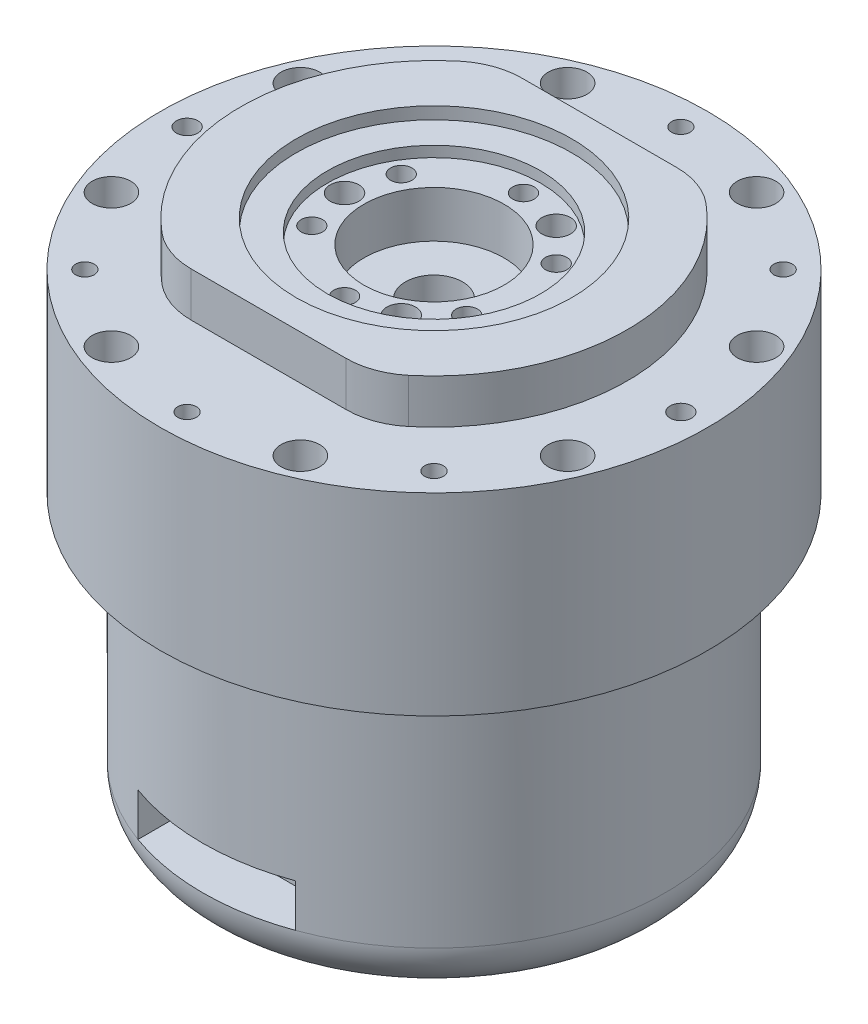
SolidWorks part; units mm, degrees
ref_plane "前视基准面" through (0, 0, 0) normal (0, 0, 1) x (1, 0, 0)
ref_plane "上视基准面" through (0, 0, 0) normal (0, 1, 0) x (1, 0, 0)
ref_plane "右视基准面" through (0, 0, 0) normal (1, 0, 0) x (0, 0, -1)
other "Configuration Table"
sketch "草图1" plane through (0, 0, 0) normal (0, 1, 0) x (1, 0, 0)
  line L0 (-38.25, 0) -> (38.25, 0) construction
  line L1 (-13.9782, 23.1) -> (13.9782, 23.1)
  line L2 (-13.9782, -23.1) -> (13.9782, -23.1)
  line L3 (0, 12.5) -> (0, 0) construction
  line L4 (0, 0) -> (6.25, 10.8253) construction
  line L5 (13.2026, 31.8738) -> (0, 0) construction
  line L6 (0, 0) -> (0, 34.5) construction
  circle A0 centre (0, 0) radius 12.5 construction
  circle A1 centre (0, 0) radius 38.25
  circle A2 centre (0, 0) radius 34.5 construction
  circle A3 centre (0, 0) radius 27
  circle A4 centre (0, 34.5) radius 1.3
  circle A5 centre (24.3952, 24.3952) radius 1.3
  circle A6 centre (34.5, 0) radius 1.3
  circle A7 centre (24.3952, -24.3952) radius 1.3
  circle A8 centre (0, -34.5) radius 1.3
  circle A9 centre (-24.3952, -24.3952) radius 1.3
  circle A10 centre (-34.5, 0) radius 1.3
  circle A11 centre (-24.3952, 24.3952) radius 1.3
  circle A12 centre (0, 12.5) radius 1.5
  circle A13 centre (10.8253, 6.25) radius 1.5
  circle A14 centre (10.8253, -6.25) radius 1.5
  circle A15 centre (0, -12.5) radius 1.5
  circle A16 centre (-10.8253, -6.25) radius 1.5
  circle A17 centre (-10.8253, 6.25) radius 1.5
  circle A18 centre (6.25, 10.8253) radius 2
  circle A19 centre (6.25, -10.8253) radius 2
  circle A20 centre (-12.5, 0) radius 2
  circle A21 centre (0, 0) radius 19.25
  circle A22 centre (0, 0) radius 14.9 construction
  circle A23 centre (0, 0) radius 9.8 construction
  circle A24 centre (13.2026, 31.8738) radius 2.7
  circle A25 centre (31.8738, 13.2026) radius 2.7
  circle A26 centre (31.8738, -13.2026) radius 2.7
  circle A27 centre (13.2026, -31.8738) radius 2.7
  circle A28 centre (-13.2026, -31.8738) radius 2.7
  circle A29 centre (-31.8738, -13.2026) radius 2.7
  circle A30 centre (-31.8738, 13.2026) radius 2.7
  circle A31 centre (-13.2026, 31.8738) radius 2.7
  point P30 (0, 0)
  point P43 (0, 0)
  point P50 (0, 0)
  point P70 (0, 0)
  dimension "D1" = 25
  dimension "D2" = 76.5
  dimension "D3" = 69
  dimension "D4" = 54
  dimension "D6" = 2.6
  dimension "D8" = 3
  dimension "D11" = 4
  dimension "D13" = 38.5
  dimension "D14" = 29.8
  dimension "D15" = 19.6
  dimension "D16" = 5.4
  dimension "D5" = 46.2
  dimension "D10" = 30
  dimension "D17" = 22.5
  dimension "D7" = 8
  dimension "D9" = 6
  dimension "D12" = 3
  dimension "D18" = 8
sketch "草图2" plane through (0, 0, 0) normal (0, 1, 0) x (1, 0, 0)
  circle A3 centre (0, 34.5) radius 1.3
  circle A4 centre (0, 34.5) radius 1.3
  circle A7 centre (0, 0) radius 38.25
  circle A8 centre (0, 0) radius 38.25
  circle A9 centre (-24.3952, 24.3952) radius 1.3
  circle A10 centre (-24.3952, 24.3952) radius 1.3
  circle A11 centre (-34.5, 0) radius 1.3
  circle A12 centre (-34.5, 0) radius 1.3
  circle A13 centre (-24.3952, -24.3952) radius 1.3
  circle A14 centre (-24.3952, -24.3952) radius 1.3
  circle A15 centre (0, -34.5) radius 1.3
  circle A16 centre (0, -34.5) radius 1.3
  circle A17 centre (24.3952, -24.3952) radius 1.3
  circle A18 centre (24.3952, -24.3952) radius 1.3
  circle A19 centre (34.5, 0) radius 1.3
  circle A20 centre (34.5, 0) radius 1.3
  circle A21 centre (24.3952, 24.3952) radius 1.3
  circle A22 centre (24.3952, 24.3952) radius 1.3
  dimension "D2" = 0
  dimension "D4" = 0
  dimension "D5" = 0
  dimension "D6" = 0
  dimension "D7" = 0
  dimension "D8" = 0
  dimension "D9" = 0
  dimension "D10" = 0
  dimension "D11" = 0
extrude "凸台-拉伸1" add sketch "草图2" along normal blind 27
cosmetic thread "装饰螺纹线2" parameters "D2"=3
cosmetic thread "装饰螺纹线3" parameters "D2"=3
cosmetic thread "装饰螺纹线4" parameters "D2"=3
cosmetic thread "装饰螺纹线5" parameters "D2"=3
cosmetic thread "装饰螺纹线6" parameters "D2"=3
cosmetic thread "装饰螺纹线7" parameters "D2"=3
sketch "草图3" plane through (0, 27, 0) normal (0, 1, 0) x (1, 0, 0)
  line L0 (-13.9782, 23.1) -> (13.9782, 23.1) construction
  line L1 (-13.9782, 23.1) -> (13.9782, 23.1)
  line L2 (-13.9782, -23.1) -> (13.9782, -23.1) construction
  line L3 (-13.9782, -23.1) -> (13.9782, -23.1)
  circle A0 centre (0, 0) radius 27 construction
  arc A1 (-13.9782, 23.1) -> (-13.9782, -23.1) centre (0, 0) ccw
  arc A2 (13.9782, -23.1) -> (13.9782, 23.1) centre (0, 0) ccw
extrude "凸台-拉伸2" add sketch "草图3" along normal blind 6.2
sketch "草图4" plane through (0, 33.2, 0) normal (0, 1, 0) x (1, 0, 0)
  circle A0 centre (0, 0) radius 19.25 construction
  circle A1 centre (0, 0) radius 19.25
  dimension "D1" = 38.5
extrude "切除-拉伸1" cut sketch "草图4" against normal blind 1.7
sketch "草图5" plane through (0, 33.2, 0) normal (0, 1, 0) x (1, 0, 0)
  circle A0 centre (0, 0) radius 14.9 construction
  circle A1 centre (0, 0) radius 14.9
extrude "切除-拉伸2" cut sketch "草图5" against normal blind 3.2
sketch "草图6" plane through (0, 30, 0) normal (0, 1, 0) x (1, 0, 0)
  circle A0 centre (0, -12.5) radius 1.5 construction
  circle A1 centre (10.8253, -6.25) radius 1.5 construction
  circle A2 centre (10.8253, 6.25) radius 1.5 construction
  circle A3 centre (-10.8253, -6.25) radius 1.5 construction
  circle A4 centre (-10.8253, 6.25) radius 1.5 construction
  circle A5 centre (0, 12.5) radius 1.5 construction
  circle A6 centre (0, -12.5) radius 1.5
  circle A7 centre (10.8253, -6.25) radius 1.5
  circle A8 centre (10.8253, 6.25) radius 1.5
  circle A9 centre (-10.8253, -6.25) radius 1.5
  circle A10 centre (-10.8253, 6.25) radius 1.5
  circle A11 centre (0, 12.5) radius 1.5
  dimension "D1" = 25
  dimension "D2" = 12.5
extrude "切除-拉伸3" cut sketch "草图6" against normal blind 8
cosmetic thread "装饰螺纹线8" parameters "D2"=3
cosmetic thread "装饰螺纹线9" parameters "D2"=3
cosmetic thread "装饰螺纹线10" parameters "D2"=3
cosmetic thread "装饰螺纹线11" parameters "D2"=3
cosmetic thread "装饰螺纹线12" parameters "D2"=3
cosmetic thread "装饰螺纹线13" parameters "D2"=3
sketch "草图7" plane through (0, 30, 0) normal (0, 1, 0) x (1, 0, 0)
  circle A0 centre (-12.5, 0) radius 2 construction
  circle A1 centre (6.25, -10.8253) radius 2 construction
  circle A2 centre (6.25, 10.8253) radius 2 construction
  circle A3 centre (-12.5, 0) radius 2
  circle A4 centre (6.25, -10.8253) radius 2
  circle A5 centre (6.25, 10.8253) radius 2
extrude "切除-拉伸4" cut sketch "草图7" against normal blind 4.5
sketch "草图8" plane through (0, 0, 0) normal (0, 1, 0) x (1, 0, 0)
  circle A0 centre (0, 0) radius 32.3
  dimension "D1" = 64.6
extrude "凸台-拉伸3" add sketch "草图8" along direction (0, 1, 0) on the side against the normal blind 39.3
fillet "圆角1" radius 7 1 edges at (0, -39.3, 32.3)
fillet "圆角2" radius 10 4 edges at (-13.9782, 30.1, -23.1) (13.9782, 30.1, 23.1) (-13.9782, 30.1, 23.1) (13.9782, 30.1, -23.1)
ref_plane "基准面1" through (0, 0, 40) normal (0, 0, 1) x (1, 0, 0)
ref_plane "基准面2" through (0, 0, -40) normal (0, 0, 1) x (1, 0, 0)
sketch "草图9" plane through (0, 0, 40) normal (0, 0, 1) x (1, 0, 0)
  line L0 (32.3, -32.3) -> (-32.3, -32.3) construction
  line L1 (-11, -26.3) -> (11, -26.3)
  line L2 (-11, -26.3) -> (-11, -32.3)
  line L3 (-11, -32.3) -> (11, -32.3)
  line L4 (11, -26.3) -> (11, -32.3)
  line L5 (-11, -26.3) -> (11, -32.3) construction
  line L6 (-11, -32.3) -> (11, -26.3) construction
  point P0 (0, -29.3)
  dimension "D1" = 22
  dimension "D2" = 6
extrude "切除-拉伸5" cut sketch "草图9" against normal blind 15
sketch "草图10" plane through (0, 0, -40) normal (0, 0, 1) x (1, 0, 0)
  line L0 (32.3, -32.3) -> (-32.3, -32.3) construction
  line L1 (11, -37.3) -> (-11, -37.3)
  line L2 (11, -37.3) -> (11, -24.3)
  line L3 (11, -24.3) -> (-11, -24.3)
  line L4 (-11, -37.3) -> (-11, -24.3)
  line L5 (11, -37.3) -> (-11, -24.3) construction
  line L6 (11, -24.3) -> (-11, -37.3) construction
  point P0 (0, -30.8)
  dimension "D1" = 22
  dimension "D2" = 8
  dimension "D3" = 5
extrude "切除-拉伸6" cut sketch "草图10" along normal blind 15
sketch "草图12" plane through (0, 30, 0) normal (0, 1, 0) x (1, 0, 0)
  circle A0 centre (0, 0) radius 9.8 construction
  circle A1 centre (0, 0) radius 9.8
extrude "切除-拉伸7" cut sketch "草图12" against normal blind 6.5
sketch "草图13" plane through (0, 23.5, 0) normal (0, 1, 0) x (1, 0, 0)
  circle A0 centre (0, 0) radius 4
  dimension "D1" = 8
extrude "切除-拉伸8" cut sketch "草图13" against normal blind 6
sketch "草图14" plane through (0, 27, 0) normal (0, 1, 0) x (1, 0, 0)
  circle A0 centre (31.8738, 13.2026) radius 2.7 construction
  circle A1 centre (31.8738, -13.2026) radius 2.7 construction
  circle A2 centre (13.2026, -31.8738) radius 2.7 construction
  circle A3 centre (-13.2026, -31.8738) radius 2.7 construction
  circle A4 centre (-31.8738, -13.2026) radius 2.7 construction
  circle A5 centre (-31.8738, 13.2026) radius 2.7 construction
  circle A6 centre (-13.2026, 31.8738) radius 2.7 construction
  circle A7 centre (13.2026, 31.8738) radius 2.7 construction
  circle A8 centre (31.8738, 13.2026) radius 2.7
  circle A9 centre (31.8738, -13.2026) radius 2.7
  circle A10 centre (13.2026, -31.8738) radius 2.7
  circle A11 centre (-13.2026, -31.8738) radius 2.7
  circle A12 centre (-31.8738, -13.2026) radius 2.7
  circle A13 centre (-31.8738, 13.2026) radius 2.7
  circle A14 centre (-13.2026, 31.8738) radius 2.7
  circle A15 centre (13.2026, 31.8738) radius 2.7
extrude "切除-拉伸9" cut sketch "草图14" against normal blind 7
sketch "草图15" plane through (0, 0, 0) normal (0, -1, 0) x (1, 0, 0)
  circle A0 centre (13.2026, 31.8738) radius 1.2
  circle A1 centre (-13.2026, 31.8738) radius 1.2
  circle A2 centre (-31.8738, 13.2026) radius 1.2
  circle A3 centre (-31.8738, -13.2026) radius 1.2
  circle A4 centre (-13.2026, -31.8738) radius 1.2
  circle A5 centre (13.2026, -31.8738) radius 1.2
  circle A6 centre (31.8738, -13.2026) radius 1.2
  circle A7 centre (31.8738, 13.2026) radius 1.2
  dimension "D1" = 2.4
extrude "切除-拉伸10" cut sketch "草图15" against normal blind 4
cosmetic thread "装饰螺纹线15" parameters "D2"=2.5
cosmetic thread "装饰螺纹线16" parameters "D2"=2.5
cosmetic thread "装饰螺纹线17" parameters "D2"=2.5
cosmetic thread "装饰螺纹线18" parameters "D2"=2.5
cosmetic thread "装饰螺纹线19" parameters "D2"=2.5
cosmetic thread "装饰螺纹线20" parameters "D2"=2.5
cosmetic thread "装饰螺纹线21" parameters "D2"=2.5
cosmetic thread "装饰螺纹线23" parameters "D2"=2.5
sketch "草图16" plane through (0, 0, 0) normal (0, -1, 0) x (1, 0, 0)
  circle A1 centre (-24.3952, -24.3952) radius 1.3 construction
  circle A2 centre (0, -34.5) radius 1.3 construction
  circle A3 centre (24.3952, -24.3952) radius 1.3 construction
  circle A5 centre (24.3952, 24.3952) radius 1.3 construction
  circle A6 centre (0, 34.5) radius 1.3 construction
  circle A7 centre (-24.3952, 24.3952) radius 1.3 construction
  circle A9 centre (-24.3952, -24.3952) radius 1.3
  circle A10 centre (0, -34.5) radius 1.3
  circle A11 centre (24.3952, -24.3952) radius 1.3
  circle A13 centre (24.3952, 24.3952) radius 1.3
  circle A14 centre (0, 34.5) radius 1.3
  circle A15 centre (-24.3952, 24.3952) radius 1.3
  circle A16 centre (0, 34.5) radius 1.2
  circle A17 centre (0, -34.5) radius 1.2
  dimension "D1" = 2.4
extrude "凸台-拉伸4" add sketch "草图16" against normal blind 12
cosmetic thread "装饰螺纹线14" parameters "D2"=2.5
cosmetic thread "装饰螺纹线22" parameters "D2"=2.5
ref_plane "基准面3" through (0, 8, 0) normal (0, -1, 0) x (-1, 0, 0)
sketch "草图18" plane through (0, 8, 0) normal (0, -1, 0) x (-1, 0, 0)
  circle A0 centre (34.5, 0) radius 1.3 construction
  circle A1 centre (-34.5, 0) radius 1.3 construction
  circle A2 centre (34.5, 0) radius 1.3
  circle A3 centre (-34.5, 0) radius 1.3
extrude "凸台-拉伸5" add sketch "草图18" against normal blind 9
sketch "草图19" plane through (0, 27, 0) normal (0, 1, 0) x (1, 0, 0)
  circle A0 centre (-34.5, 0) radius 1.5
  circle A1 centre (34.5, 0) radius 1.5
  dimension "D1" = 3
extrude "切除-拉伸11" cut sketch "草图19" against normal up to surface (10 mm away) up to face at (-34.5, 17, -1.3)
sketch "草图20" plane through (0, 27, 0) normal (0, 1, 0) x (1, 0, 0)
  circle A0 centre (0, 0) radius 38.25 construction
  circle A1 centre (0, 0) radius 38.25
  dimension "D1" = 76.5
